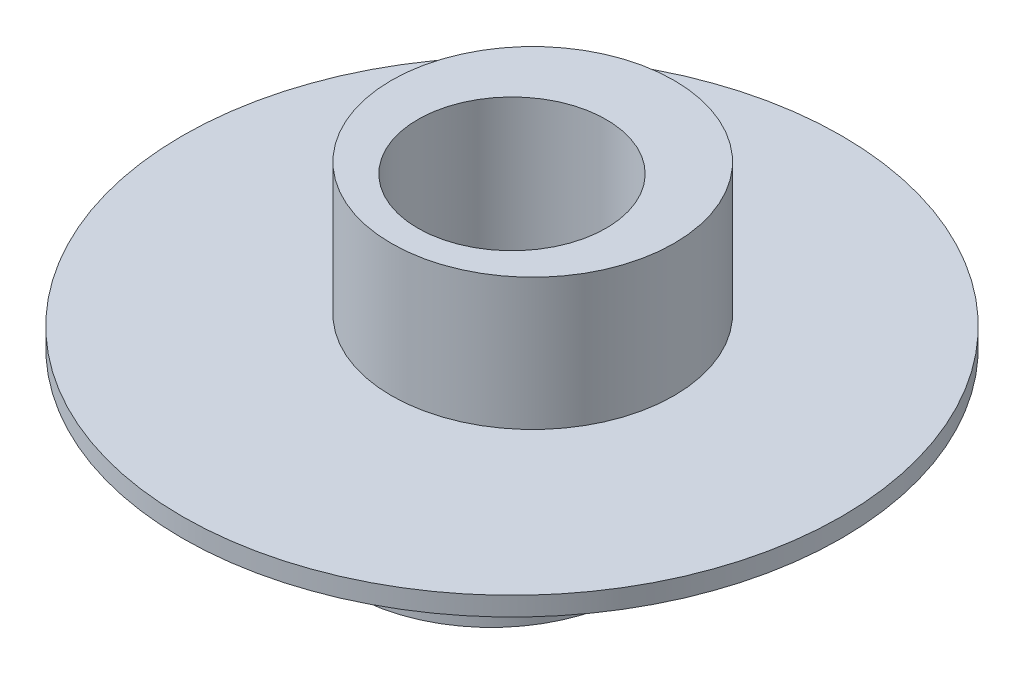
SolidWorks part; units mm, degrees
ref_plane "Front Plane" through (0, 0, 0) normal (0, 0, 1) x (1, 0, 0)
ref_plane "Top Plane" through (0, 0, 0) normal (0, 1, 0) x (1, 0, 0)
ref_plane "Right Plane" through (0, 0, 0) normal (1, 0, 0) x (0, 0, -1)
sketch "Sketch1" plane through (0, 0, 0) normal (0, 1, 0) x (1, 0, 0)
  circle A0 centre (0, 0) radius 5
  dimension "D1" = 10
extrude "Boss-Extrude1" add sketch "Sketch1" along normal blind 13
sketch "Sketch2" plane through (0, 13, 0) normal (0, 1, 0) x (1, 0, 0)
  line L0 (0, 0) -> (0, -1.1) construction
  circle A0 centre (0, -1.1) radius 7.5
  dimension "D1" = 15
  dimension "D2" = 1.1
extrude "Boss-Extrude2" add sketch "Sketch2" along normal blind 8
sketch "Sketch3" plane through (0, 21, 0) normal (0, 1, 0) x (1, 0, 0)
  line L0 (0, 0) -> (0, 1.1) construction
  circle A0 centre (0, 1.1) radius 7.5
  dimension "D1" = 1.1
  dimension "D2" = 15
extrude "Boss-Extrude3" add sketch "Sketch3" along normal blind 7
sketch "Sketch4" plane through (0, 28, 0) normal (0, 1, 0) x (1, 0, 0)
  circle A0 centre (0, 0) radius 5
  dimension "D1" = 10
extrude "Boss-Extrude4" add sketch "Sketch4" along normal blind 13
sketch "Sketch5" plane through (0, 0, 0) normal (0, -1, 0) x (1, 0, 0)
  circle A0 centre (0, 0) radius 5
extrude "Cut-Extrude1" cut sketch "Sketch5" against normal through all
sketch "Sketch6" plane through (0, 21, 0) normal (0, -1, 0) x (1, 0, 0)
  circle A0 centre (0, 0) radius 17.5
  dimension "D1" = 35
extrude "Boss-Extrude5" add sketch "Sketch6" along normal blind 1
sketch "Sketch7" plane through (0, 21, 0) normal (0, 1, 0) x (1, 0, 0)
  circle A0 centre (0, 0) radius 5
extrude "Cut-Extrude2" cut sketch "Sketch7" against normal through all
